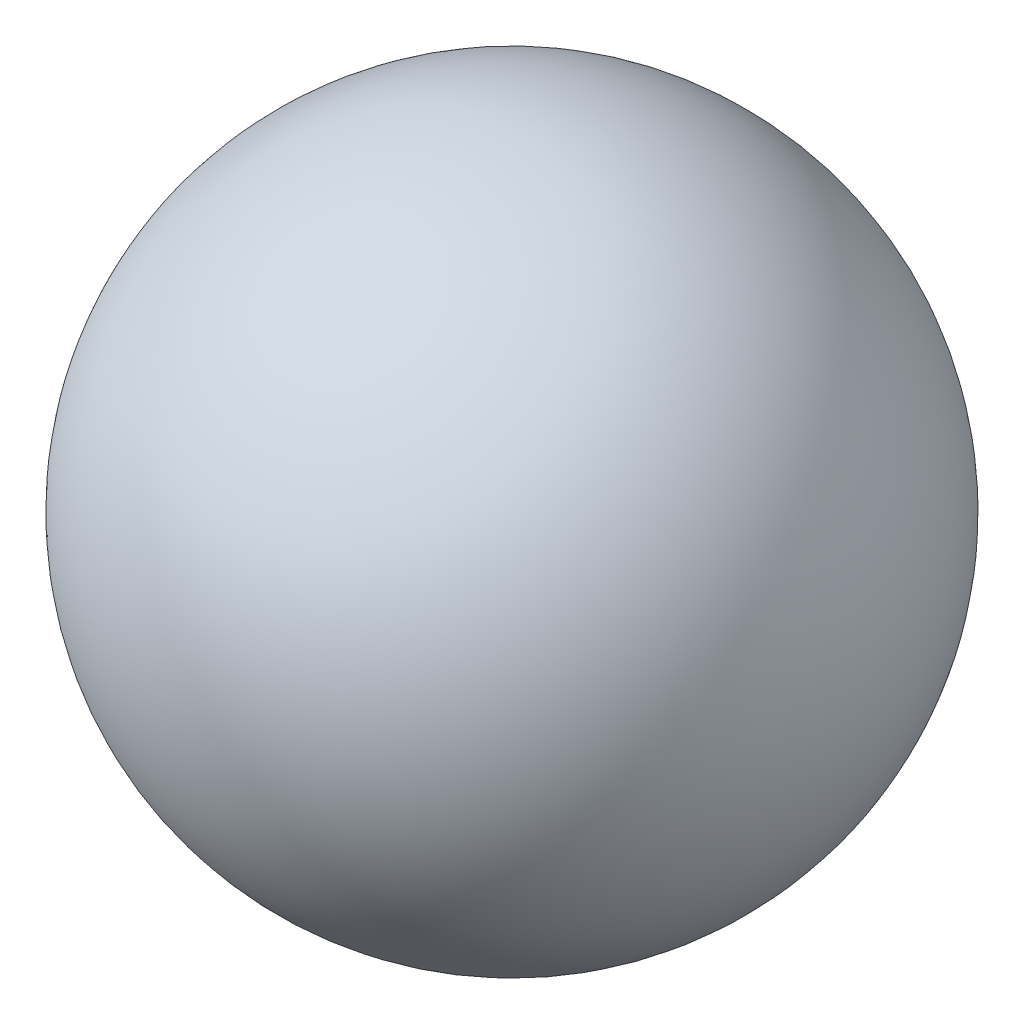
SolidWorks part; units mm, degrees
ref_plane "Front Plane" through (0, 0, 0) normal (0, 0, 1) x (1, 0, 0)
ref_plane "Top Plane" through (0, 0, 0) normal (0, 1, 0) x (1, 0, 0)
ref_plane "Right Plane" through (0, 0, 0) normal (1, 0, 0) x (0, 0, -1)
sketch "Sketch1" plane through (0, 0, 0) normal (0, 0, 1) x (1, 0, 0)
  line L0 (0, 0) -> (24, 0)
  arc A0 (0, 0) -> (24, 0) centre (12, 0) ccw
  dimension "D1" = 24
revolve "Revolve1" add sketch "Sketch1" angle 360 about L0
